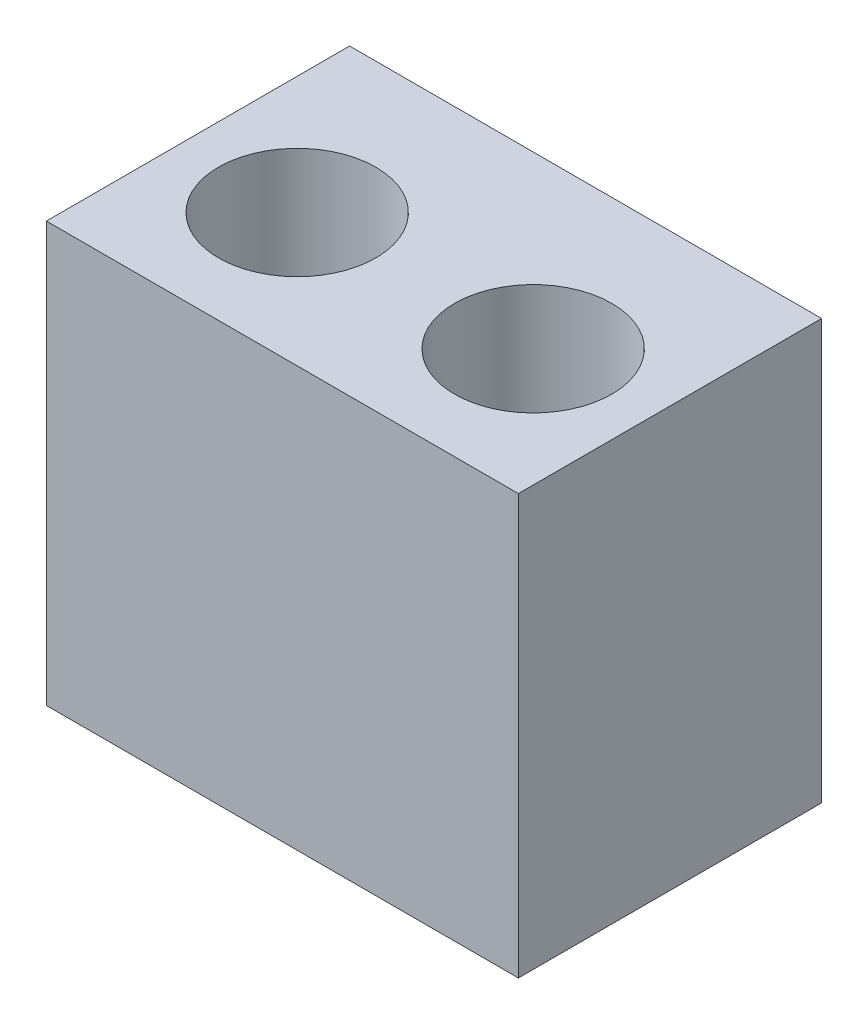
SolidWorks part; units mm, degrees
ref_plane "Front Plane" through (0, 0, 0) normal (0, 0, 1) x (1, 0, 0)
ref_plane "Top Plane" through (0, 0, 0) normal (0, 1, 0) x (1, 0, 0)
ref_plane "Right Plane" through (0, 0, 0) normal (1, 0, 0) x (0, 0, -1)
sketch "Sketch1" plane through (0, 0, 0) normal (0, 0, 1) x (1, 0, 0)
  line L0 (181.8841, 13.5886) -> (136.8841, 13.5886)
  line L1 (136.8841, 13.5886) -> (136.8841, 53.5886)
  line L2 (136.8841, 53.5886) -> (181.8841, 53.5886)
  line L3 (181.8841, 53.5886) -> (181.8841, 13.5886)
  line L7 (174.6341, 53.5886) -> (166.6341, 53.5886) construction
  dimension "D1" = 45
  dimension "D2" = 40
extrude "Boss-Extrude1" add sketch "Sketch1" along normal up to surface (28.91 mm away)
sketch "Sketch2" plane through (0, 13.5886, 0) normal (0, -1, 0) x (1, 0, 0)
  line L0 (136.8841, 28.91) -> (136.8841, 0) construction
  line L2 (181.8841, 28.91) -> (181.8841, 0) construction
  circle A0 centre (148.1341, 16.25) radius 7.5
  circle A2 centre (170.6341, 16.25) radius 7.5
  dimension "D3" = 15
  dimension "D4" = 11.25
  dimension "D1" = 11.25
extrude "Cut-Extrude1" cut sketch "Sketch2" against normal through all
